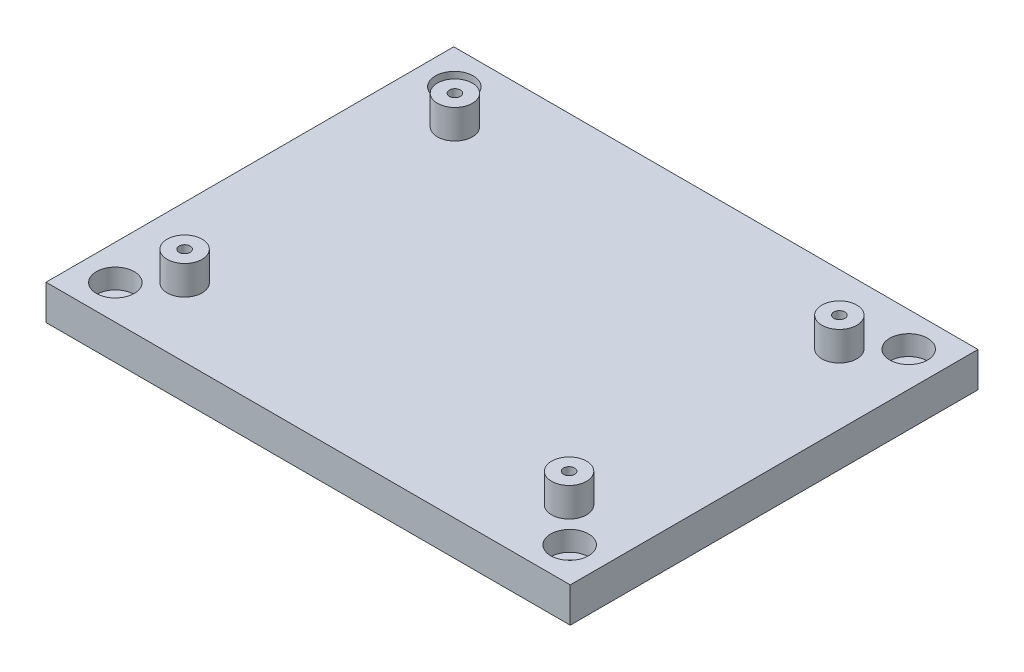
SolidWorks part; units mm, degrees
ref_plane "Front Plane" through (0, 0, 0) normal (0, 0, 1) x (1, 0, 0)
ref_plane "Top Plane" through (0, 0, 0) normal (0, 1, 0) x (1, 0, 0)
ref_plane "Right Plane" through (0, 0, 0) normal (1, 0, 0) x (0, 0, -1)
sketch "Szkic1" plane through (0, 0, 0) normal (0, 1, 0) x (1, 0, 0)
  line L0 (-45, -35) -> (45, 35) construction
  line L1 (-45, 35) -> (45, 35)
  line L2 (-45, 35) -> (-45, -35)
  line L3 (-45, -35) -> (45, -35)
  line L4 (45, 35) -> (45, -35)
  dimension "D1" = 70
  dimension "D2" = 90
extrude "Dodanie-wyciągnięcie1" add sketch "Szkic1" along normal blind 6
sketch "Szkic2" plane through (0, 6, 0) normal (0, 1, 0) x (1, 0, 0)
  circle A0 centre (-33, 23.2) radius 3
  circle A1 centre (-33, -23.2) radius 3
  circle A2 centre (33, -23.2) radius 3
  circle A3 centre (33, 23.2) radius 3
  circle A4 centre (33, 23.2) radius 0.95
  circle A5 centre (-33, 23.2) radius 0.95
  circle A6 centre (-33, -23.2) radius 0.95
  circle A7 centre (33, -23.2) radius 0.95
  dimension "D1" = 6
  dimension "D2" = 1.9
extrude "Dodanie-wyciągnięcie2" add sketch "Szkic2" along normal blind 5
hole_wizard "CBORE for M3 Hex Socket Head Cap Screw1" positions "Szkic3" profile "Szkic4" counterbore size "M3" standard "DIN"
sketch "Szkic3" plane through (0, 6, 0) normal (0, 1, 0) x (1, 0, 0)
  line L2 (-33, 23.2) -> (-45, 35) construction
  line L5 (33, -23.2) -> (45, -35) construction
  point P0 (-39, 29.1)
  point P2 (-39, -29.1)
  point P4 (39, 29.1)
  point P6 (39, -29.1)
  point P35 (0, 0)
  point P36 (0, 0)
  point P37 (0, 0)
  point P44 (0, 0)
sketch "Szkic4" plane through (-39, 6, -29.1) normal (1, 0, 0) x (0, 0, 1)
  line L0 (0, 0) -> (0, 18.6614)
  line L1 (0, 18.6614) -> (1.6, 17.7)
  line L2 (1.6, 17.7) -> (1.6, 3.4)
  line L3 (1.6, 3.4) -> (3.25, 3.4)
  line L4 (3.25, 3.4) -> (3.25, 0)
  line L5 (3.25, 0) -> (0, 0)
  line L10 (0, 18.6614) -> (-1.6, 17.7) construction
  line L11 (0, -6.35) -> (0, 107.95) construction
  dimension "Hole Dia." = 3.2
  dimension "Hole Depth" = 17.7
  dimension "C'Bore Dia." = 6.5
  dimension "C'Bore Depth" = 3.4
  dimension "Drill Angle" = 118
